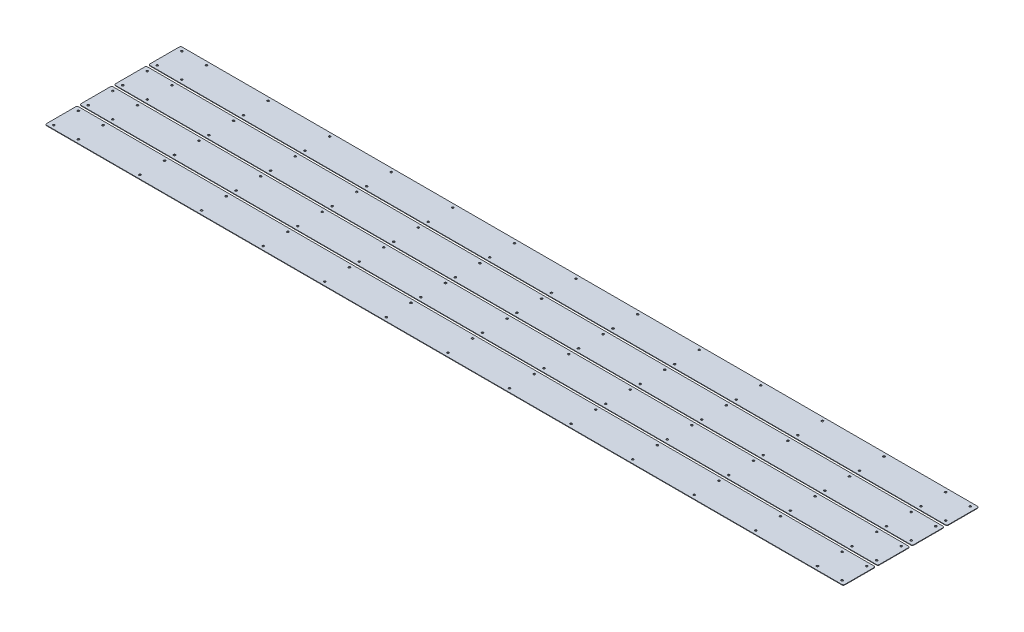
SolidWorks part; units mm, degrees
ref_plane "Front Plane" through (0, 0, 0) normal (0, 0, 1) x (1, 0, 0)
ref_plane "Top Plane" through (0, 0, 0) normal (0, 1, 0) x (1, 0, 0)
ref_plane "Right Plane" through (0, 0, 0) normal (1, 0, 0) x (0, 0, -1)
sketch "Sketch1" plane through (0, 0, 0) normal (0, 1, 0) x (1, 0, 0)
  line L0 (0, 0) -> (0, 50) construction
  line L1 (-800, 50) -> (-800, 0) construction
  line L2 (-810, -7.5) -> (810, -7.5)
  line L3 (-810, -7.5) -> (-810, 57.5)
  line L4 (-810, 57.5) -> (810, 57.5)
  line L5 (810, -7.5) -> (810, 57.5)
  line L6 (-810, -7.5) -> (810, 57.5) construction
  line L7 (-810, 57.5) -> (810, -7.5) construction
  line L8 (-800, 25) -> (0, 25) construction
  line L9 (0, 25) -> (800, 25) construction
  line L10 (800, 50) -> (800, 0) construction
  line L11 (750, 50) -> (800, 50) construction
  line L12 (-800, 50) -> (-750, 50) construction
  circle A0 centre (0, 0) radius 2
  circle A1 centre (0, 50) radius 2
  circle A2 centre (125, 0) radius 2
  circle A3 centre (125, 50) radius 2
  circle A4 centre (250, 0) radius 2
  circle A5 centre (250, 50) radius 2
  circle A6 centre (375, 0) radius 2
  circle A7 centre (375, 50) radius 2
  circle A8 centre (500, 0) radius 2
  circle A9 centre (500, 50) radius 2
  circle A10 centre (625, 0) radius 2
  circle A11 centre (625, 50) radius 2
  circle A12 centre (750, 0) radius 2
  circle A13 centre (750, 50) radius 2
  circle A14 centre (-125, 0) radius 2
  circle A15 centre (-125, 50) radius 2
  circle A16 centre (-250, 0) radius 2
  circle A17 centre (-250, 50) radius 2
  circle A18 centre (-375, 0) radius 2
  circle A19 centre (-375, 50) radius 2
  circle A20 centre (-500, 0) radius 2
  circle A21 centre (-500, 50) radius 2
  circle A22 centre (-625, 0) radius 2
  circle A23 centre (-625, 50) radius 2
  circle A24 centre (-750, 0) radius 2
  circle A25 centre (-750, 50) radius 2
  circle A26 centre (-800, 50) radius 2
  circle A27 centre (-800, 0) radius 2
  circle A28 centre (800, 50) radius 2
  circle A29 centre (800, 0) radius 2
  point P5 (0, 25)
  dimension "D1" = 50
  dimension "D2" = 4
  dimension "D9" = 4
  dimension "D12" = 4
  dimension "D3" = 7.5
  dimension "D4" = 1620
  dimension "D7" = 125
  dimension "D8" = 125
  dimension "D10" = 10
  dimension "D11" = 10
  dimension "D5" = 7
  dimension "D6" = 7
extrude "Boss-Extrude1" add sketch "Sketch1" along normal blind 1
fillet "Fillet1" radius 3 4 edges at (810, 0.5, -57.5) (810, 0.5, 7.5) (-810, 0.5, -57.5) (-810, 0.5, 7.5)
pattern_linear "LPattern1" count 4 spacing 70 along (0, 0, -1) of bodies 101
